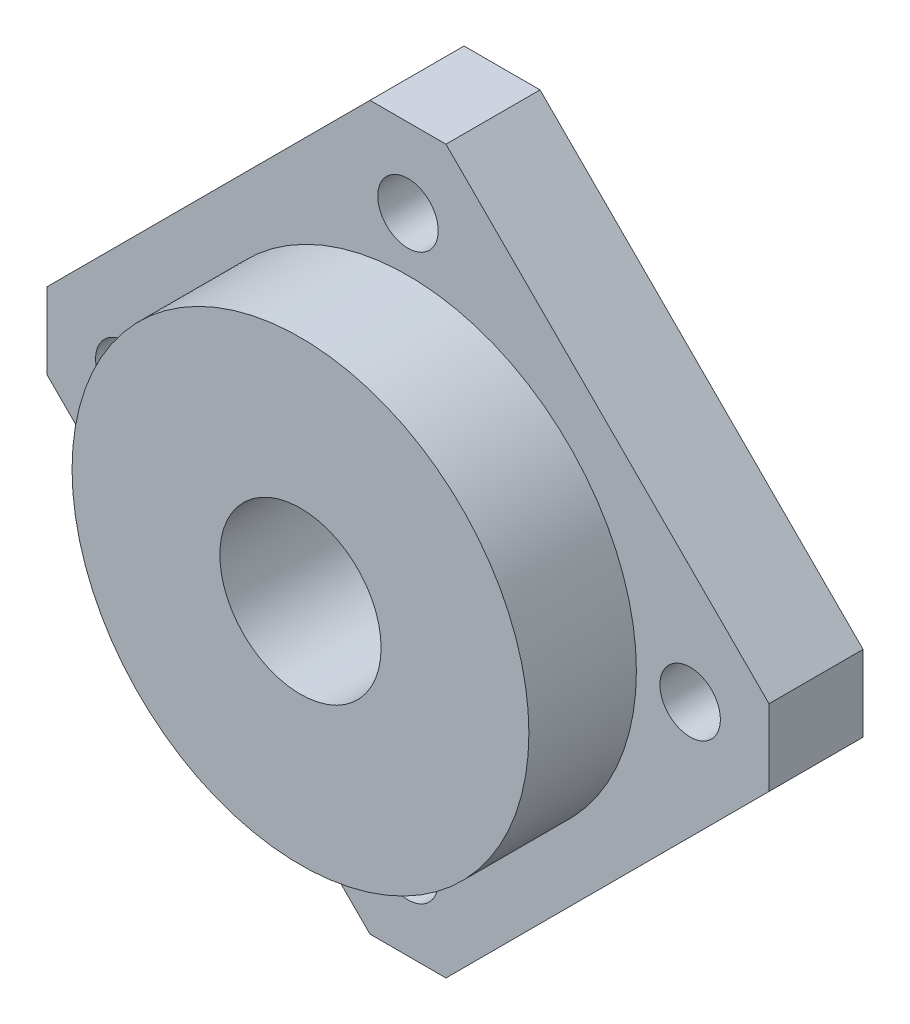
SolidWorks part; units mm, degrees
ref_plane "Front Plane" through (0, 0, 0) normal (0, 0, 1) x (1, 0, 0)
ref_plane "Top Plane" through (0, 0, 0) normal (0, 1, 0) x (1, 0, 0)
ref_plane "Right Plane" through (0, 0, 0) normal (1, 0, 0) x (0, 0, -1)
ref_plane "Plane1"
sketch "Sketch1" plane through (0, 0, 0) normal (0, 0, 1) x (1, 0, 0)
  line L0 (-29.6985, 0) -> (0, 29.6985)
  line L1 (0, 29.6985) -> (29.6985, 0)
  line L2 (29.6985, 0) -> (0, -29.6985)
  line L3 (0, -29.6985) -> (-29.6985, 0)
  dimension "D1" = 42
  dimension "D2" = 42
extrude "Extrusion1" add sketch "Sketch1" along normal blind 7
sketch "Sketch2" plane through (0, 0, 7) normal (0, 0, 1) x (1, 0, 0)
  circle A0 centre (0, 21) radius 2.25
  circle A1 centre (21, 0) radius 2.25
  circle A2 centre (0, -21) radius 2.25
  circle A3 centre (-21, 0) radius 2.25
  dimension "D1" = 4.5
  dimension "D2" = 4.5
  dimension "D3" = 4.5
  dimension "D4" = 4.5
  dimension "D5" = 29.6985
  dimension "D6" = 29.6985
  dimension "D7" = 29.6985
  dimension "D8" = 21
extrude "Extrusion2" cut sketch "Sketch2" against normal blind 20 contours A0 | A1 | A2 | A3
sketch "Sketch3" plane through (0, 0, 7) normal (0, 0, 1) x (1, 0, 0)
  circle A0 centre (0, 0) radius 6
  dimension "D1" = 12
extrude "Extrusion3" cut sketch "Sketch3" against normal blind 20
ref_plane "Plane2"
sketch "Sketch4" plane through (0, 0, 7) normal (0, 0, 1) x (1, 0, 0)
  circle A0 centre (0, 0) radius 17
  circle A1 centre (0, 0) radius 6
  dimension "D1" = 34
extrude "Extrusion4" add sketch "Sketch4" along normal blind 8 contours A0 A1
chamfer "Chamfer1" distance 4 distance2 4 1 edges at (0, 29.6985, 3.5)
chamfer "Chamfer2" distance 4 distance2 4 1 edges at (29.6985, 0, 3.5)
chamfer "Chamfer3" distance 4 distance2 4 1 edges at (-29.6985, 0, 3.5)
chamfer "Chamfer4" distance 4 distance2 4 1 edges at (0, -29.6985, 3.5)
